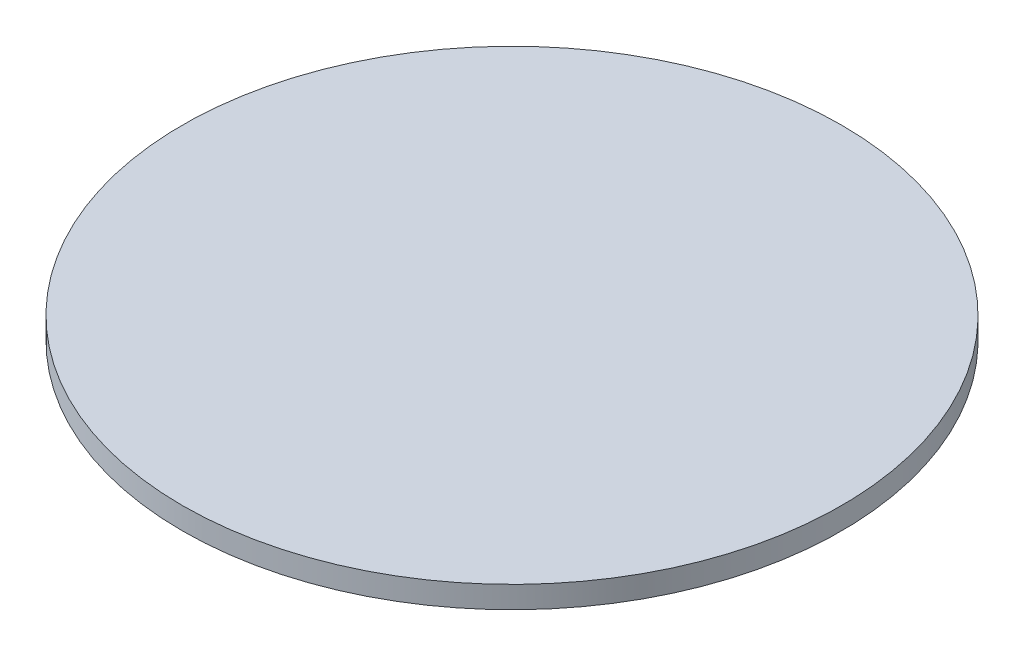
SolidWorks part; units mm, degrees
ref_plane "Front Plane" through (0, 0, 0) normal (0, 0, 1) x (1, 0, 0)
ref_plane "Top Plane" through (0, 0, 0) normal (0, 1, 0) x (1, 0, 0)
ref_plane "Right Plane" through (0, 0, 0) normal (1, 0, 0) x (0, 0, -1)
sketch "Sketch1" plane through (0, 0, 0) normal (0, 1, 0) x (1, 0, 0)
  circle A0 centre (0, 0) radius 75
  dimension "D1" = 150
extrude "Boss-Extrude1" add sketch "Sketch1" along normal blind 5
